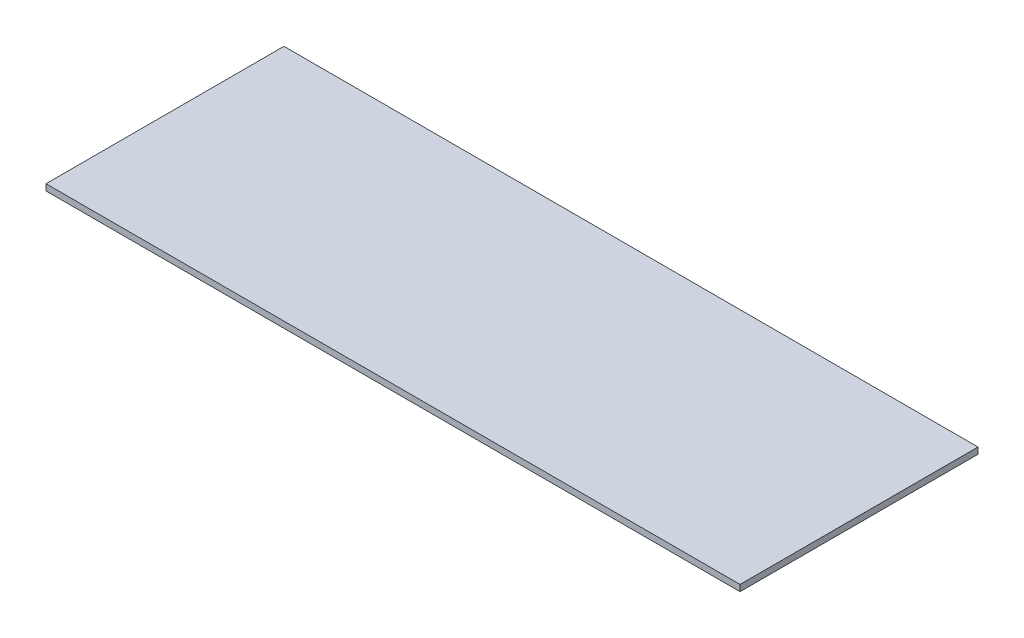
SolidWorks part; units mm, degrees
material "Pine"
ref_plane "Front Plane" through (0, 0, 0) normal (0, 0, 1) x (1, 0, 0)
ref_plane "Top Plane" through (0, 0, 0) normal (0, 1, 0) x (1, 0, 0)
ref_plane "Right Plane" through (0, 0, 0) normal (1, 0, 0) x (0, 0, -1)
sketch "Sketch1" plane through (0, 0, 0) normal (0, 1, 0) x (1, 0, 0)
  line L1 (0, 0) -> (1400, 0)
  line L2 (0, 0) -> (0, 480)
  line L3 (0, 480) -> (1400, 480)
  line L4 (1400, 0) -> (1400, 480)
  dimension "D1" = 1400
  dimension "D2" = 480
extrude "Boss-Extrude1" add sketch "Sketch1" along normal blind 12.7
